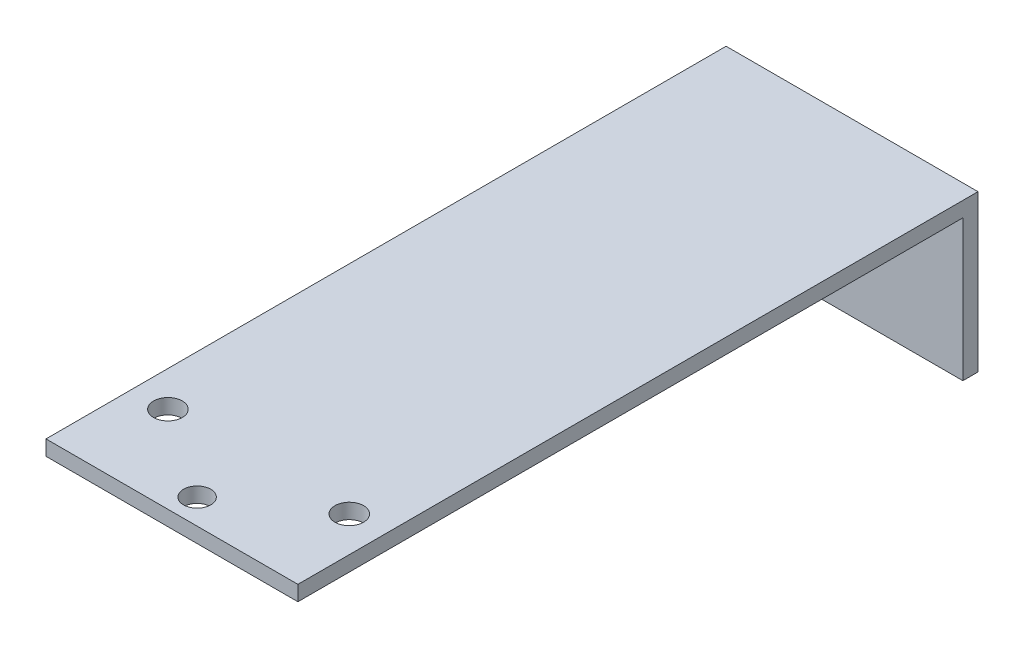
SolidWorks part; units mm, degrees
ref_plane "Front Plane" through (0, 0, 0) normal (0, 0, 1) x (1, 0, 0)
ref_plane "Top Plane" through (0, 0, 0) normal (0, 1, 0) x (1, 0, 0)
ref_plane "Right Plane" through (0, 0, 0) normal (1, 0, 0) x (0, 0, -1)
sketch "Sketch1" plane through (0, 0, 0) normal (0, 1, 0) x (1, 0, 0)
  line L1 (-47.4392, 55.5122) -> (2.5608, 55.5122)
  line L2 (-47.4392, 55.5122) -> (-47.4392, -79.4878)
  line L3 (-47.4392, -79.4878) -> (2.5608, -79.4878)
  line L4 (2.5608, 55.5122) -> (2.5608, -79.4878)
  dimension "D1" = 135
  dimension "D2" = 50
extrude "Boss-Extrude1" add sketch "Sketch1" along normal blind 3
sketch "Sketch2" plane through (0, 0, 0) normal (0, -1, 0) x (1, 0, 0)
  line L0 (2.5608, 79.4878) -> (2.5608, -55.5122) construction
  line L1 (-47.4392, -55.5122) -> (2.5608, -55.5122)
  line L2 (-47.4392, -55.5122) -> (-47.4392, -52.5122)
  line L3 (-47.4392, -52.5122) -> (2.5608, -52.5122)
  line L4 (2.5608, -55.5122) -> (2.5608, -52.5122)
  dimension "D1" = 3
extrude "Boss-Extrude2" add sketch "Sketch2" along normal blind 28
sketch "Sketch3" plane through (0, 0, 0) normal (0, -1, 0) x (1, 0, 0)
  line L0 (-22.4392, -52.5122) -> (-22.4392, 74.4878) construction
  line L1 (2.5608, -52.5122) -> (-47.4392, -52.5122) construction
  circle A0 centre (-22.4392, 74.4878) radius 2.7
  dimension "D2" = 5.4
  dimension "D1" = 127
extrude "Cut-Extrude1" cut sketch "Sketch3" against normal blind 90
sketch "Sketch5" plane through (0, 0, 0) normal (0, -1, 0) x (1, 0, 0)
  line L0 (-22.4392, 74.4878) -> (-22.4392, 67.9878) construction
  line L1 (-22.4392, 67.9878) -> (-22.4392, 62.2878) construction
  line L2 (-22.4392, 62.2878) -> (-40.4392, 62.2878) construction
  line L3 (-22.4392, 62.2878) -> (-4.4392, 62.2878) construction
  circle A0 centre (-40.4392, 62.2878) radius 2.85
  circle A1 centre (-4.4392, 62.2878) radius 2.85
  dimension "D5" = 5.7
  dimension "D6" = 5.7
  dimension "D1" = 6.5
  dimension "D2" = 5.7
  dimension "D3" = 18
  dimension "D4" = 18
extrude "Cut-Extrude2" cut sketch "Sketch5" against normal blind 90
